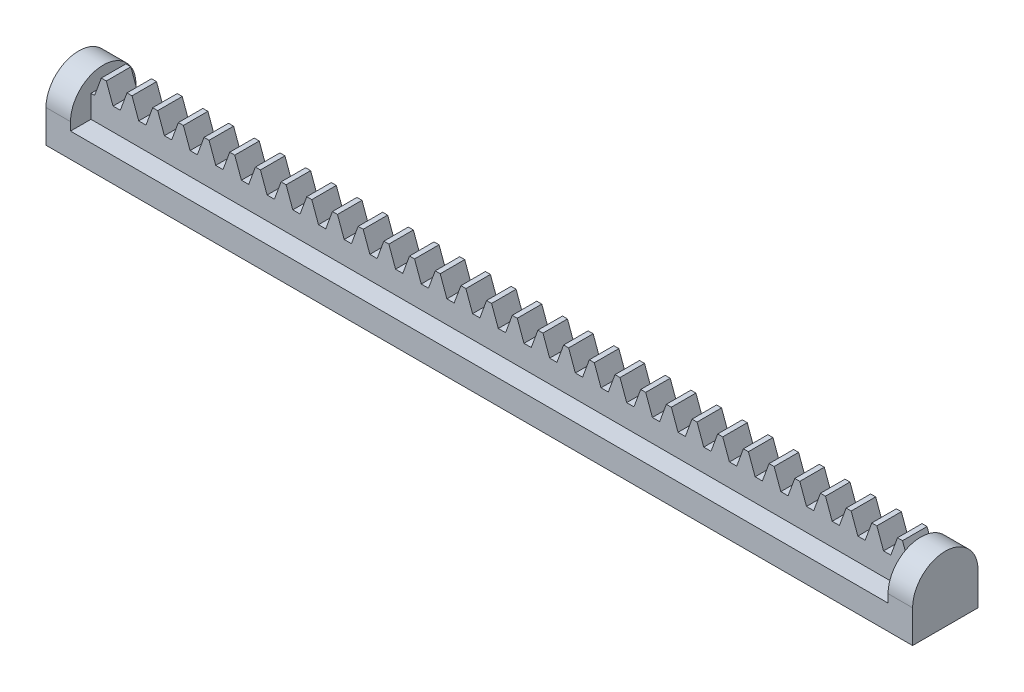
SolidWorks part; units mm, degrees
extrude "Blank" add sketch "BlankSke" against normal blind 3
sketch "BlankSke" plane through (0, 0, 0) normal (0, 0, 1) x (1, 0, 0)
  line L1 (0, 0) -> (100, 0)
  line L2 (0, 0) -> (0, 8)
  line L3 (0, 8) -> (100, 8)
  line L4 (100, 0) -> (100, 8)
  dimension "Length" = 100
  dimension "Blank_height" = 8
ref_plane "Plane1" through (0, 0, 0) normal (0, 0, 1) x (1, 0, 0)
ref_plane "Plane2" through (0, 0, 0) normal (0, 1, 0) x (1, 0, 0)
ref_plane "Plane3" through (0, 0, 0) normal (1, 0, 0) x (0, 0, -1)
sketch "HoldingSke" plane through (0, 0, 0) normal (0, 1, 0) x (1, 0, 0)
  line L0 (0, 0) -> (0.1392, 0.9903)
  line L1 (-15, 0) -> (100, 0) construction
  line L2 (0, 0) -> (-2.1039, 2.3779)
  line L3 (0, 0) -> (-11.863, 4.5341)
  line L4 (0, 0) -> (7.2428, 4.7035)
  line L5 (0, 0) -> (-23.7986, -8.8762)
  line L6 (0, 0) -> (-10.5278, -7.1032)
  line L9 (-71.009, 38.7566) -> (22.9603, 72.9586)
  line L10 (-76.2, 3.3779) -> (-69.2, 3.3779)
  line L11 (0, 0) -> (-3, 0)
  line L12 (-76.2, 101.6) -> (-76.162, 101.6)
  line L13 (24.9733, 27.94) -> (52.9518, 28.4284)
  line L14 (24.9733, 27.94) -> (24.9743, 27.94)
  line L15 (24.9733, 27.94) -> (100.4006, 29.5858)
  circle A0 centre (0, 0) radius 19.05
  circle A1 centre (0, 0) radius 3.5
  circle A2 centre (0, 0) radius 12.7
  dimension "MPH" = 7
  dimension "Diameter" = 38.1
  dimension "Num_teeth" = 33
  dimension "Pitch" = 1
  dimension "Show_teeth" = 998
  dimension "Thickness" = 12.7
  dimension "Ap" = 20
  dimension "Pitch_height" = 7
  dimension "Width" = 3
  dimension "Backlash" = 0.038
  dimension "Addendum_fac" = 1
  dimension "Dedendum_fac" = 1.25
  dimension "Clearance_fac" = 0.25
  dimension "Dedendum_add" = 0.001
  dimension "Length" = 100
  dimension "Module" = 1
sketch "TooCutSkeIll" plane through (0, 0, 0) normal (0, 0, 1) x (1, 0, 0)
  line L0 (-1.2538, 7.9737) -> (-0.5045, 5.9152)
  line L1 (-0.2687, 5.75) -> (0.2687, 5.75)
  line L2 (0.5045, 5.9152) -> (1.2538, 7.9737)
  line L3 (100, 8) -> (0, 8) construction
  line L4 (0, 0) -> (0, 64.897) construction
  line L5 (-13.208, 7) -> (12.954, 7) construction
  line L6 (0, 0) -> (100, 0) construction
  line L7 (0.8994, 7) -> (0.8994, 48.7463) construction
  line L8 (-0.8994, 7) -> (-0.8994, 48.7463) construction
  line L9 (1.2914, 8) -> (1.2914, 8.0254)
  line L10 (-1.2914, 8) -> (-1.2914, 8.0254)
  line L11 (-1.2914, 8.0254) -> (1.2914, 8.0254)
  arc A0 (0.2687, 5.75) -> (0.5045, 5.9152) centre (0.2687, 6.001) ccw
  arc A1 (-0.5045, 5.9152) -> (-0.2687, 5.75) centre (-0.2687, 6.001) ccw
  arc A2 (1.2914, 8) -> (1.2538, 7.9737) centre (1.2914, 7.96) ccw
  arc A3 (-1.2538, 7.9737) -> (-1.2914, 8) centre (-1.2914, 7.96) ccw
  dimension "Pitch_height" = 7
  dimension "Addendum_plus" = 1.0254
  dimension "Pressure_angle" = 20
  dimension "Gap_width" = 1.7988
  dimension "Dedendum" = 1.25
extrude "ToothCutIll" [suppressed] cut sketch "TooCutSkeIll" against normal through all
sketch "TooCutSkeSim" plane through (0, 0, 0) normal (0, 0, 1) x (1, 0, 0)
  line L0 (0.4444, 5.75) -> (-0.4444, 5.75)
  line L1 (1.2726, 8.0254) -> (0.4444, 5.75)
  line L2 (0, 17.4625) -> (0, 53.467) construction
  line L3 (1.2726, 8.0254) -> (-1.2726, 8.0254)
  line L6 (-1.2726, 8.0254) -> (-0.4444, 5.75)
  line L9 (-0.8994, 7) -> (0.8994, 7) construction
  line L10 (0, 0) -> (100, 0) construction
  line L11 (0.8994, 7) -> (0.8994, 53.467) construction
  line L12 (-0.8994, 7) -> (-0.8994, 53.467) construction
  dimension "Pitch_height" = 7
  dimension "Addendum_plus" = 1.0254
  dimension "Pressure_angle" = 20
  dimension "Gap_width" = 1.7988
  dimension "Dedendum" = 1.25
extrude "ToothCutSim" cut sketch "TooCutSkeSim" against normal through all
pattern_linear "TeethCuts" count 32 spacing 3.1416 along (1, 0, 0) of "ToothCutIll", "ToothCutSim"
sketch "Esquisse1" plane through (0, 0, 0) normal (0, 0, 1) x (1, 0, 0)
  line L1 (0, 0) -> (100, 0)
  line L2 (0, 0) -> (0, 3)
  line L3 (0, 3) -> (100, 3)
  line L4 (100, 0) -> (100, 3)
  line L5 (100, 0) -> (100, 5.9877) construction
  point P5 (100, 0)
  point P7 (0, 0)
  point P8 (0, 0)
  dimension "D1" = 3
extrude "Boss.-Extru.1" add sketch "Esquisse1" along normal blind 2.5
sketch "Esquisse2" plane through (0, 0, -3) normal (0, 0, -1) x (-1, 0, 0)
  line L1 (-100, 0) -> (0, 0)
  line L2 (-100, 0) -> (-100, 3)
  line L3 (-100, 3) -> (0, 3)
  line L4 (0, 0) -> (0, 3)
extrude "Boss.-Extru.2" add sketch "Esquisse2" along normal blind 2.5
sketch "Esquisse3" plane through (100, 0, 0) normal (1, 0, 0) x (0, 0, -1)
  line L0 (-2.5, 0) -> (5.5, 0)
  line L1 (5.5, 0) -> (5.5, 4)
  line L3 (-2.5, 0) -> (-2.5, 4)
  arc A0 (-2.5, 4) -> (5.5, 4) centre (1.5, 4) cw
  dimension "D1" = 4
extrude "Boss.-Extru.3" add sketch "Esquisse3" along normal blind 3
sketch "Esquisse4" plane through (0, 0, 0) normal (-1, 0, 0) x (0, 0, 1)
  line L0 (-5.5, 4) -> (-5.5, 0)
  line L1 (-5.5, 0) -> (2.5, 0)
  line L2 (2.5, 0) -> (2.5, 4)
  line L3 (2.5, 4) -> (2.5, 3) construction
  arc A0 (-5.5, 4) -> (2.5, 4) centre (-1.5, 4) cw
  dimension "D1" = 4
extrude "Boss.-Extru.4" add sketch "Esquisse4" along normal blind 3
equation "' \"Module@HoldingSke\" = 6.35"
equation "' \"Num_teeth@HoldingSke\" = 12"
equation "' \"Ap@HoldingSke\" =  20"
equation "' \"Ap@HoldingSke\" = 20"
equation "' \"Width@HoldingSke\" = 0.25 * 25.4"
equation "' \"Show_teeth@HoldingSke\" = 500"
equation "' \"Backlash@HoldingSke\" = 0.009 * 25.4"
equation "' \"Addendum_fac@HoldingSke\" = 1.0"
equation "' \"Dedendum_fac@HoldingSke\" = 1.25"
equation "' \"Dedendum_add@HoldingSke\" = 0.00005 * 25.4"
equation "' \"Clearance_fac@HoldingSke\" = 0.25"
equation "' \"Pitch_height@HoldingSke\" = 1 * 25.4"
equation "' \"Length@HoldingSke\" = 4.71 * 25.4"
equation "\"Pitch@HoldingSke\" = 1 / \"Module@HoldingSke\""
equation "\"MPH@HoldingSke\" = \"Dedendum_fac@HoldingSke\" / \"Pitch@HoldingSke\" + 2 * \"Dedendum_add@HoldingSke\" + 0.002 * 25.4"
equation "\"MPH@HoldingSke\" = ((sgn( \"MPH@HoldingSke\" - \"Pitch_height@HoldingSke\")+1)*( \"MPH@HoldingSke\" - \"Pitch_height@HoldingSke\"))/2 + \"Pitch_height@HoldingSke\""
equation "\"Blank_height@BlankSke\" = \"Pitch_height@HoldingSke\" + \"Addendum_fac@HoldingSke\"  / \"Pitch@HoldingSke\" "
equation "\"Length@BlankSke\" =  \"Length@HoldingSke\""
equation "\"Face_width@Blank\" = \"Width@HoldingSke\""
equation "\"Pressure_angle@TooCutSkeIll\" = \"Ap@HoldingSke\""
equation "\"Addendum_plus@TooCutSkeIll\" =  \"Addendum_fac@HoldingSke\"  / \"Pitch@HoldingSke\" + 0.001 *25.4"
equation "\"Dedendum@TooCutSkeIll\" = \"Dedendum_fac@HoldingSke\"  / \"Pitch@HoldingSke\""
equation "\"Pitch_height@TooCutSkeIll\" =  \"MPH@HoldingSke\""
equation "\"Gap_width@TooCutSkeIll\" = 3.14159265 / 2 / \"Pitch@HoldingSke\" + 6 * \"Backlash@HoldingSke\""
equation "\"Pressure_angle@TooCutSkeSim\" = \"Ap@HoldingSke\""
equation "\"Addendum_plus@TooCutSkeSim\" =  \"Addendum_fac@HoldingSke\"  / \"Pitch@HoldingSke\" + 0.001 * 25.4"
equation "\"Dedendum@TooCutSkeSim\" = \"Dedendum_fac@HoldingSke\"  / \"Pitch@HoldingSke\""
equation "\"Pitch_height@TooCutSkeSim\" =  \"MPH@HoldingSke\""
equation "\"Gap_width@TooCutSkeSim\" = 3.14159265 / 2 / \"Pitch@HoldingSke\" + 6 * \"Backlash@HoldingSke\""
equation "\"Root_fillet@TooCutSkeIll\" = \"Clearance_fac@HoldingSke\" / \"Pitch@HoldingSke\" + \"Dedendum_add@HoldingSke\""
equation "\"Break_rad@TooCutSkeIll\" = 0.02 / \"Pitch@HoldingSke\" * 2"
equation "\"Linear_pitch@TeethCuts\" = 3.14159265 / \"Pitch@HoldingSke\""
equation "\"Num_teeth@HoldingSke\" = int( ( \"Length@HoldingSke\" + 0 ) / (3.14159265 / \"Pitch@HoldingSke\")) + 0.9999  + 1"
equation " \"Num_teeth@TeethCuts\" = int( \"Show_teeth@HoldingSke\" ) + 1"
equation " \"Num_teeth@TeethCuts\" = ((sgn( \"Num_teeth@TeethCuts\" - \"Num_teeth@HoldingSke\" )-1)*( \"Num_teeth@TeethCuts\" - \"Num_teeth@HoldingSke\" ))/-2+ \"Num_teeth@HoldingSke\""
equation " \"Num_teeth@TeethCuts\" = ((sgn( \"Num_teeth@TeethCuts\" - 2.0)+1)*( \"Num_teeth@TeethCuts\" - 2.0))/2 +2.0"
